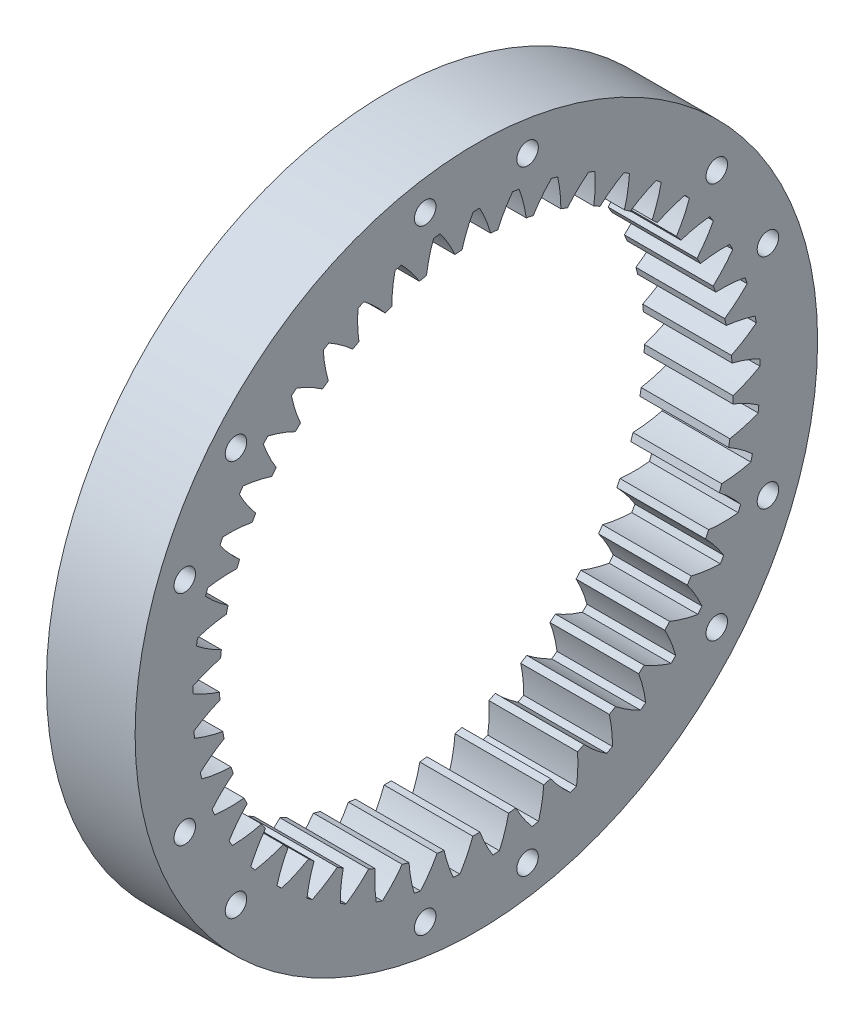
SolidWorks part; units mm, degrees
ref_plane "Plane1" through (0, 0, 0) normal (0, 0, 1) x (1, 0, 0)
ref_plane "Plane2" through (0, 0, 0) normal (0, 1, 0) x (1, 0, 0)
ref_plane "Plane3" through (0, 0, 0) normal (1, 0, 0) x (0, 0, -1)
sketch "HoldingSke" plane through (0, 0, 0) normal (0, 1, 0) x (1, 0, 0)
  line L0 (0, 0) -> (0.4041, -0.4041)
  line L1 (-15, 0) -> (100, 0) construction
  line L2 (0, 0) -> (-2.1039, 2.3779)
  line L3 (0, 0) -> (-11.863, 4.5341)
  line L4 (0, 0) -> (6.1066, 6.1066)
  line L5 (0, 0) -> (-23.7986, -8.8762)
  line L6 (0, 0) -> (-10.5278, -7.1032)
  line L7 (-2.1039, 2.3779) -> (3.3635, 27.1825)
  line L8 (-76.2, 4.1279) -> (-54.61, 4.1279)
  line L9 (-71.009, 38.7566) -> (-53.1078, 45.2721)
  line L10 (-76.2, 71.12) -> (104.1128, 71.12)
  line L11 (0, 0) -> (-13, 0)
  line L12 (-76.2, 101.6) -> (-76.147, 101.6)
  line L13 (24.9733, 27.94) -> (52.9518, 28.4284)
  line L14 (24.9733, 27.94) -> (24.9743, 27.94)
  line L15 (24.9733, 27.94) -> (100.4006, 29.5858)
  circle A0 centre (0, 0) radius 15
  circle A1 centre (0, 0) radius 12.7
  circle A2 centre (0, 0) radius 12.7
  dimension "MHD" = 25.4
  dimension "Hub_dia" = 25.4
  dimension "Diameter" = 30
  dimension "Num_teeth" = 45
  dimension "Pitch" = 0.5714
  dimension "Overall_len" = 25.4
  dimension "Show_teeth" = 45
  dimension "Thickness" = 12.7
  dimension "OAL" = 25.4001
  dimension "T_dim" = 21.59
  dimension "Ap" = 20
  dimension "H" = 19.05
  dimension "Pitch_radius" = 180.3128
  dimension "Width" = 13
  dimension "Backlash" = 0.053
  dimension "Addendum_fac" = 1
  dimension "Dedendum_fac" = 1.25
  dimension "Clearance_fac" = 0.25
  dimension "Dedendum_add" = 0.001
  dimension "Module" = 1.75
sketch "BasProSke" plane through (0, 0, 0) normal (0, 1, 0) x (1, 0, 0)
  line L0 (-10, 0) -> (60, 0) construction
  line L1 (0, 37.625) -> (0, 41.5889)
  line L2 (0, 37.625) -> (13, 37.625)
  line L3 (13, 37.625) -> (13, 41.5889)
  line L4 (13, 41.5889) -> (0, 41.5889)
  dimension "Thickness" = 13
  dimension "Diameter" = 83.1778
  dimension "Inside_diameter" = 75.25
revolve "Base-Revolve" add sketch "BasProSke" angle 360 about L0
sketch "TooCutSke" plane through (0, 0, 0) normal (1, 0, 0) x (0, 0, -1)
  line L3 (1.5067, 39.3462) -> (1.5067, 53.6633) construction
  line L4 (0, 0) -> (0, 59.563) construction
  line L5 (0, 0) -> (-4.7663, 68.1611) construction
  line L6 (-16.8397, 32.2041) -> (35.4277, 35.859) construction
  circle A0 centre (0, 0) radius 39.375 construction
  circle A1 centre (0, 0) radius 41.5635 construction
  circle A2 centre (0, 0) radius 33.3004 construction
  circle A3 centre (0, 0) radius 37.5996 construction
  arc A4 (2.1108, 37.5403) -> (0.4823, 41.5607) centre (-16.8397, 32.2041) ccw
  arc A5 (2.1108, 37.5403) -> (-2.1108, 37.5403) centre (0, 0) ccw
  arc A6 (0.4823, 41.5607) -> (-0.4823, 41.5607) centre (0, 0) ccw
  arc A7 (-0.4823, 41.5607) -> (-2.1108, 37.5403) centre (16.8397, 32.2041) ccw
  dimension "Pitch_dia" = 78.75
  dimension "Base_dia" = 66.6007
  dimension "Root_dia" = 83.127
  dimension "Overcut_dia" = 75.1992
  dimension "Flank_rad" = 19.6875
  dimension "Half_ang" = 4
  dimension "Half_CT" = 1.5067
extrude "ToothCut" cut sketch "TooCutSke" along normal through all
fillet "Breaks" [suppressed] radius 0.175
fillet "RootFillets" [suppressed] radius 0.4385
pattern_circular "TeethCuts" count 45 every 8 about axis through (-10, 0, 0) along (1, 0, 0) of "RootFillets", "Breaks", "ToothCut"
sketch "Sketch1" plane through (13, 0, 0) normal (1, 0, 0) x (0, 0, -1)
  circle A0 centre (0, 0) radius 41.5889
  circle A1 centre (0, 0) radius 50
  circle A2 centre (0, 0) radius 41.5889 construction
  dimension "D1" = 100
extrude "Boss-Extrude1" add sketch "Sketch1" against normal up to surface (13 mm away) up to face at (0, 0, 41.5889)
sketch "Sketch3" plane through (0, 0, 0) normal (-1, 0, 0) x (0, 0, 1)
  line L0 (-7.5, -45) -> (7.5, -45) construction
  line L1 (0, -45) -> (0, 0) construction
  circle A0 centre (-7.5, -45) radius 1.575
  circle A1 centre (7.5, -45) radius 1.575
  dimension "D1" = 3.15
  dimension "D2" = 15
  dimension "D3" = 45
extrude "Cut-Extrude1" cut sketch "Sketch3" against normal up to next
pattern_circular "CirPattern1" count 6 over 360 about axis through (0, 0, 0) along (1, 0, 0) of "Cut-Extrude1"
equation "' \"Module@HoldingSke\" = 6.35"
equation "' \"Num_teeth@HoldingSke\" = 24"
equation "' \"Ap@HoldingSke\" =  14.5"
equation "' \"Ap@HoldingSke\" = 14.5"
equation "' \"Width@HoldingSke\" = 12"
equation "' \"Diameter@HoldingSke\" = 8 * 25.4"
equation "' \"Show_teeth@HoldingSke\" = 100"
equation "' \"Backlash@HoldingSke\" = 0.009 * 25.4"
equation "' \"Addendum_fac@HoldingSke\" = 1.0"
equation "' \"Dedendum_fac@HoldingSke\" = 1.25"
equation "' \"Dedendum_add@HoldingSke\" = 0.00005 * 25.4"
equation "' \"Clearance_fac@HoldingSke\" = 0.25"
equation "\"Pitch@HoldingSke\" = 1 / \"Module@HoldingSke\" "
equation "\"Overcut_dia@TooCutSke\" = (\"Num_teeth@HoldingSke\" - 2 * \"Addendum_fac@HoldingSke\") / \"Pitch@HoldingSke\" - 0.002 * 25.4"
equation "\"Pitch_dia@TooCutSke\" = \"Num_teeth@HoldingSke\" / \"Pitch@HoldingSke\""
equation "\"Base_dia@TooCutSke\" = \"Num_teeth@HoldingSke\" / \"Pitch@HoldingSke\" * cos((\"Ap@HoldingSke\"  * 3.14159265 / 180)) * 0.90"
equation "\"Root_dia@TooCutSke\" = \"Num_teeth@HoldingSke\"  / \"Pitch@HoldingSke\" + 2 *  \"Dedendum_fac@HoldingSke\"/ \"Pitch@HoldingSke\" + \"Dedendum_add@HoldingSke\" * 2"
equation "\"Half_ang@TooCutSke\" = 180 / \"Num_teeth@HoldingSke\""
equation "\"Half_CT@TooCutSke\" = \"Num_teeth@HoldingSke\" / \"Pitch@HoldingSke\" * sin((3.14159265 / 2 / \"Num_teeth@HoldingSke\")) / 2 + 10 * \"Backlash@HoldingSke\" / 4"
equation "\"Flank_rad@TooCutSke\" = \"Num_teeth@HoldingSke\" / \"Pitch@HoldingSke\" / 4"
equation "\"Radius@RootFillets\"= \"Clearance_fac@HoldingSke\" / \"Pitch@HoldingSke\" + \"Dedendum_add@HoldingSke\""
equation "\"Break_rad@Breaks\" = 0.02 / \"Pitch@HoldingSke\" * 5"
equation "\"Num_teeth@TeethCuts\" = int( \"Show_teeth@HoldingSke\" ) + 1"
equation "\"Num_teeth@TeethCuts\" = ((sgn( \"Num_teeth@TeethCuts\" - \"Num_teeth@HoldingSke\" )-1)*( \"Num_teeth@TeethCuts\" - \"Num_teeth@HoldingSke\" ))/-2+ \"Num_teeth@HoldingSke\""
equation "\"Num_teeth@TeethCuts\" = ((sgn( \"Num_teeth@TeethCuts\" - 2.0)+1)*( \"Num_teeth@TeethCuts\" - 2.0))/2 +2.0"
equation "\"Angle@TeethCuts\" = 360.0 / \"Num_teeth@HoldingSke\""
equation "\"Diameter@BasProSke\" = \"Num_teeth@HoldingSke\"  / \"Pitch@HoldingSke\" + 2 *  \"Dedendum_fac@HoldingSke\"/ \"Pitch@HoldingSke\" + \"Dedendum_add@HoldingSke\" * 2 + 0.002 * 25.4"
equation "\"Diameter@BasProSke\" = ((sgn( \"Diameter@BasProSke\"  - \"Diameter@HoldingSke\" )+1)*( \"Diameter@BasProSke\"  - \"Diameter@HoldingSke\" ))/2 + \"Diameter@HoldingSke\""
equation "\"Inside_diameter@BasProSke\" =  (\"Num_teeth@HoldingSke\" - 2 * \"Addendum_fac@HoldingSke\") / \"Pitch@HoldingSke\" "
equation "\"Thickness@BasProSke\"  = \"Width@HoldingSke\""
